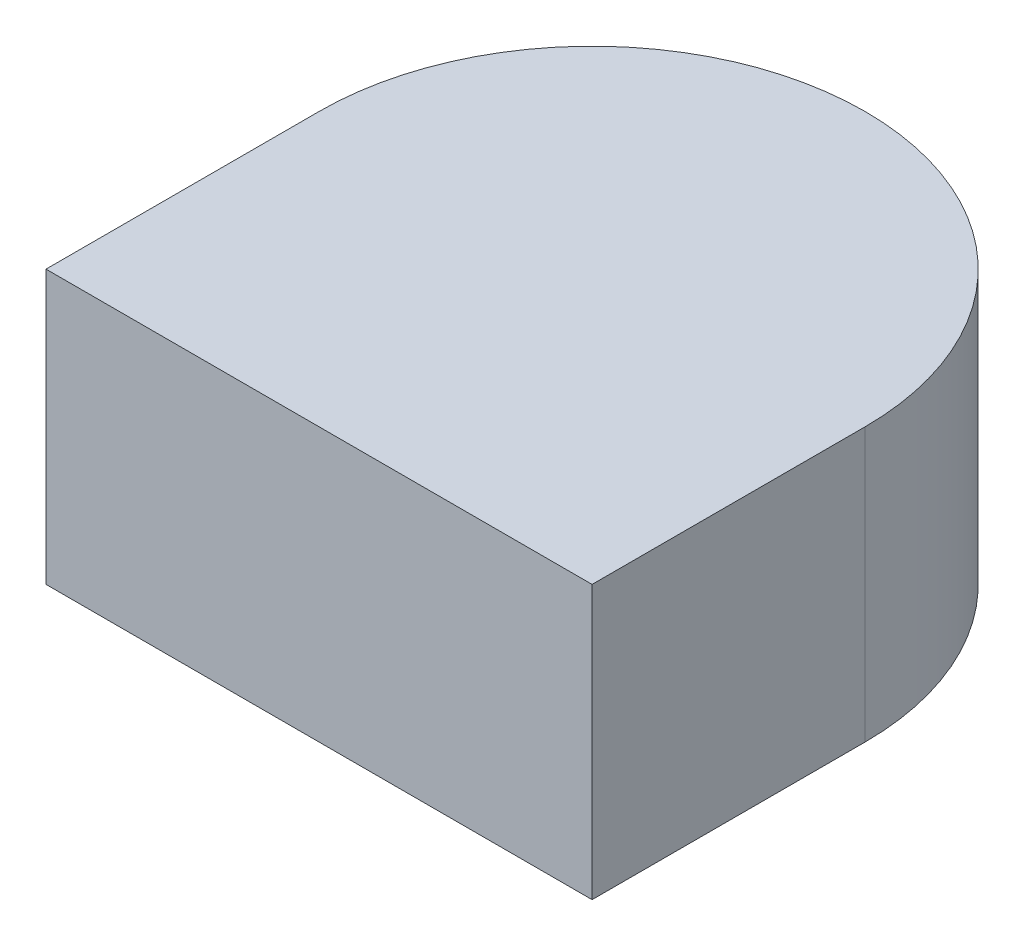
SolidWorks part; units mm, degrees
ref_plane "Přední rovina" through (0, 0, 0) normal (0, 0, 1) x (1, 0, 0)
ref_plane "Horní rovina" through (0, 0, 0) normal (0, 1, 0) x (1, 0, 0)
ref_plane "Pravá rovina" through (0, 0, 0) normal (1, 0, 0) x (0, 0, -1)
sketch "Sketch1" plane through (0, 0, 0) normal (0, 1, 0) x (1, 0, 0)
  line L1 (-20, -40) -> (20, -40)
  line L2 (-20, -40) -> (-20, -20)
  line L4 (20, -40) -> (20, -20)
  arc A0 (-20, -20) -> (20, -20) centre (0, -20) cw
  dimension "D1" = 40
  dimension "D2" = 20
extrude "Boss-Extrude1" add sketch "Sketch1" along normal blind 20
equation "\"R\"= 20'Radius"
equation "\"D1@Sketch1\"=\"R\"*2"
equation "\"D2@Sketch1\"=\"R\""
equation "\"H\"= 20'Extrude height"
equation "\"D1@Boss-Extrude1\"=\"H\""
